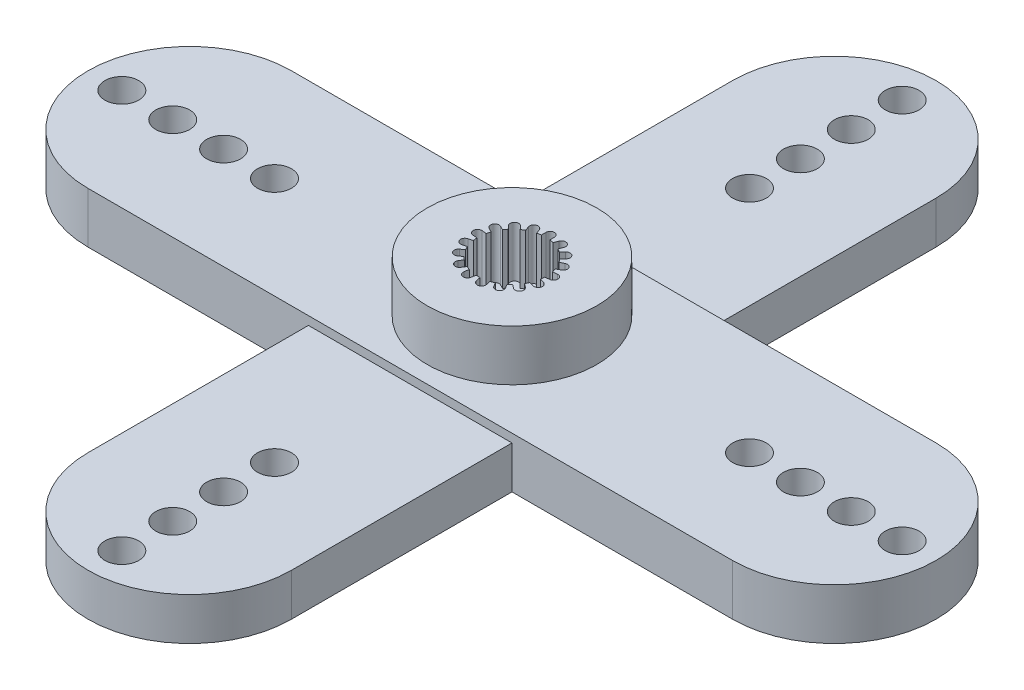
SolidWorks part; units mm, degrees
material "PP Homopolymer"
ref_plane "Front Plane" through (0, 0, 0) normal (0, 0, 1) x (1, 0, 0)
ref_plane "Top Plane" through (0, 0, 0) normal (0, 1, 0) x (1, 0, 0)
ref_plane "Right Plane" through (0, 0, 0) normal (1, 0, 0) x (0, 0, -1)
sketch "Sketch1" plane through (0, 0, 0) normal (0, 1, 0) x (1, 0, 0)
  circle A0 centre (0, 0) radius 5
  dimension "D1" = 10
extrude "Boss-Extrude1" add sketch "Sketch1" along normal blind 3
sketch "Sketch2" plane through (0, 0, 0) normal (0, -1, 0) x (1, 0, 0)
  line L0 (-19, 0) -> (19, 0) construction
  line L1 (-19, 6) -> (19, 6)
  line L2 (-19, -6) -> (19, -6)
  arc A0 (-19, 6) -> (-19, -6) centre (-19, 0) ccw
  arc A1 (19, -6) -> (19, 6) centre (19, 0) ccw
  point P2 (0, 0)
  dimension "D1" = 12
  dimension "D2" = 38
extrude "Boss-Extrude2" add sketch "Sketch2" along normal blind 3
sketch "Sketch3" plane through (0, -3, 0) normal (0, -1, 0) x (1, 0, 0)
  line L0 (0, -19) -> (0, 19) construction
  line L1 (-6, -19) -> (-6, 19)
  line L2 (6, -19) -> (6, 19)
  line L4 (19, 6) -> (-19, 6) construction
  arc A0 (-6, -19) -> (6, -19) centre (0, -19) ccw
  arc A1 (6, 19) -> (-6, 19) centre (0, 19) ccw
  arc A2 (19, -6) -> (19, 6) centre (19, 0) ccw construction
  point P2 (0, 0)
extrude "Boss-Extrude3" add sketch "Sketch3" against normal blind 2.5
sketch "Sketch4" plane through (0, -3, 0) normal (0, -1, 0) x (1, 0, 0)
  circle A0 centre (0, 0) radius 3
  dimension "D1" = 6
extrude "Cut-Extrude1" cut sketch "Sketch4" against normal blind 1
sketch "Sketch5" plane through (0, -2, 0) normal (0, -1, 0) x (1, 0, 0)
  circle A0 centre (0, 0) radius 1.25
  dimension "D1" = 2.5
extrude "Cut-Extrude2" cut sketch "Sketch5" against normal through all
sketch "Sketch6" plane through (0, 3, 0) normal (0, 1, 0) x (1, 0, 0)
  line L0 (0.25, 2.25) -> (0.25, 1.9843)
  line L1 (-0.25, 2.25) -> (-0.25, 1.9843)
  line L2 (0, 0) -> (0, 2.25) construction
  line L3 (1.0459, 2.0078) -> (0.9499, 1.76)
  line L4 (0.5797, 2.1884) -> (0.4837, 1.9406)
  line L5 (1.7006, 1.4943) -> (1.5216, 1.298)
  line L6 (1.3311, 1.8312) -> (1.1521, 1.6348)
  line L7 (2.1256, 0.7791) -> (1.8877, 0.6607)
  line L8 (1.9027, 1.2267) -> (1.6648, 1.1083)
  line L9 (2.2635, -0.0413) -> (1.9989, -0.0658)
  line L10 (2.2173, 0.4565) -> (1.9528, 0.432)
  line L11 (2.0957, -0.8562) -> (1.8401, -0.7835)
  line L12 (2.2325, -0.3753) -> (1.977, -0.3026)
  line L13 (1.6449, -1.5554) -> (1.4329, -1.3953)
  line L14 (1.9462, -1.1564) -> (1.7342, -0.9963)
  line L15 (0.9719, -2.0446) -> (0.8321, -1.8187)
  line L16 (1.397, -1.7814) -> (1.2572, -1.5555)
  line L17 (0.1677, -2.2576) -> (0.1189, -1.9965)
  line L18 (0.6592, -2.1658) -> (0.6104, -1.9046)
  line L19 (-0.6592, -2.1658) -> (-0.6104, -1.9046)
  line L20 (-0.1677, -2.2576) -> (-0.1189, -1.9965)
  line L21 (-1.397, -1.7814) -> (-1.2572, -1.5555)
  line L22 (-0.9719, -2.0446) -> (-0.8321, -1.8187)
  line L23 (-1.9462, -1.1564) -> (-1.7342, -0.9963)
  line L24 (-1.6449, -1.5554) -> (-1.4329, -1.3953)
  line L25 (-2.2325, -0.3753) -> (-1.977, -0.3026)
  line L26 (-2.0957, -0.8562) -> (-1.8401, -0.7835)
  line L27 (-2.2173, 0.4565) -> (-1.9528, 0.432)
  line L28 (-2.2635, -0.0413) -> (-1.9989, -0.0658)
  line L29 (-1.9027, 1.2267) -> (-1.6648, 1.1083)
  line L30 (-2.1256, 0.7791) -> (-1.8877, 0.6607)
  line L31 (-1.3311, 1.8312) -> (-1.1521, 1.6348)
  line L32 (-1.7006, 1.4943) -> (-1.5216, 1.298)
  line L33 (-0.5797, 2.1884) -> (-0.4837, 1.9406)
  line L34 (-1.0459, 2.0078) -> (-0.9499, 1.76)
  arc A0 (-0.25, 1.9843) -> (-0.4837, 1.9406) centre (0, 0) ccw
  arc A1 (0.25, 2.25) -> (-0.25, 2.25) centre (0, 2.25) ccw
  arc A2 (1.0459, 2.0078) -> (0.5797, 2.1884) centre (0.8128, 2.0981) ccw
  arc A3 (1.7006, 1.4943) -> (1.3311, 1.8312) centre (1.5158, 1.6628) ccw
  arc A4 (2.1256, 0.7791) -> (1.9027, 1.2267) centre (2.0141, 1.0029) ccw
  arc A5 (2.2635, -0.0413) -> (2.2173, 0.4565) centre (2.2404, 0.2076) ccw
  arc A6 (2.0957, -0.8562) -> (2.2325, -0.3753) centre (2.1641, -0.6157) ccw
  arc A7 (1.6449, -1.5554) -> (1.9462, -1.1564) centre (1.7955, -1.3559) ccw
  arc A8 (0.9719, -2.0446) -> (1.397, -1.7814) centre (1.1845, -1.913) ccw
  arc A9 (0.1677, -2.2576) -> (0.6592, -2.1658) centre (0.4134, -2.2117) ccw
  arc A10 (-0.6592, -2.1658) -> (-0.1677, -2.2576) centre (-0.4134, -2.2117) ccw
  arc A11 (-1.397, -1.7814) -> (-0.9719, -2.0446) centre (-1.1845, -1.913) ccw
  arc A12 (-1.9462, -1.1564) -> (-1.6449, -1.5554) centre (-1.7955, -1.3559) ccw
  arc A13 (-2.2325, -0.3753) -> (-2.0957, -0.8562) centre (-2.1641, -0.6157) ccw
  arc A14 (-2.2173, 0.4565) -> (-2.2635, -0.0413) centre (-2.2404, 0.2076) ccw
  arc A15 (-1.9027, 1.2267) -> (-2.1256, 0.7791) centre (-2.0141, 1.0029) ccw
  arc A16 (-1.3311, 1.8312) -> (-1.7006, 1.4943) centre (-1.5158, 1.6628) ccw
  arc A17 (-0.5797, 2.1884) -> (-1.0459, 2.0078) centre (-0.8128, 2.0981) ccw
  arc A18 (0.4837, 1.9406) -> (0.25, 1.9843) centre (0, 0) ccw
  arc A19 (1.1521, 1.6348) -> (0.9499, 1.76) centre (0, 0) ccw
  arc A20 (1.6648, 1.1083) -> (1.5216, 1.298) centre (0, 0) ccw
  arc A21 (1.9528, 0.432) -> (1.8877, 0.6607) centre (0, 0) ccw
  arc A22 (1.977, -0.3026) -> (1.9989, -0.0658) centre (0, 0) ccw
  arc A23 (-0.9499, 1.76) -> (-1.1521, 1.6348) centre (0, 0) ccw
  arc A24 (-1.5216, 1.298) -> (-1.6648, 1.1083) centre (0, 0) ccw
  arc A25 (-1.8877, 0.6607) -> (-1.9528, 0.432) centre (0, 0) ccw
  arc A26 (-1.9989, -0.0658) -> (-1.977, -0.3026) centre (0, 0) ccw
  arc A27 (-1.8401, -0.7835) -> (-1.7342, -0.9963) centre (0, 0) ccw
  arc A28 (-1.4329, -1.3953) -> (-1.2572, -1.5555) centre (0, 0) ccw
  arc A29 (-0.8321, -1.8187) -> (-0.6104, -1.9046) centre (0, 0) ccw
  arc A30 (-0.1189, -1.9965) -> (0.1189, -1.9965) centre (0, 0) ccw
  arc A31 (0.6104, -1.9046) -> (0.8321, -1.8187) centre (0, 0) ccw
  arc A32 (1.2572, -1.5555) -> (1.4329, -1.3953) centre (0, 0) ccw
  arc A33 (1.7342, -0.9963) -> (1.8401, -0.7835) centre (0, 0) ccw
  point P89 (0, 0)
  dimension "D1" = 4
  dimension "D2" = 0.5
  dimension "D3" = 2.25
  dimension "D4" = 17
extrude "Cut-Extrude3" cut sketch "Sketch6" against normal blind 3
sketch "Sketch7" plane through (0, -3, 0) normal (0, -1, 0) x (1, 0, 0)
  line L0 (0, 25) -> (0, -25) construction
  arc A0 (6, 19) -> (-6, 19) centre (0, 19) ccw construction
  arc A1 (-6, -19) -> (6, -19) centre (0, -19) ccw construction
  circle A2 centre (0, 23) radius 1
  circle A3 centre (0, 20) radius 1
  circle A4 centre (0, 17) radius 1
  circle A5 centre (0, 14) radius 1
  circle A6 centre (23, 0) radius 1
  circle A7 centre (20, 0) radius 1
  circle A8 centre (17, 0) radius 1
  circle A9 centre (14, 0) radius 1
  circle A10 centre (0, -23) radius 1
  circle A11 centre (0, -20) radius 1
  circle A12 centre (0, -17) radius 1
  circle A13 centre (0, -14) radius 1
  circle A14 centre (-23, 0) radius 1
  circle A15 centre (-20, 0) radius 1
  circle A16 centre (-17, 0) radius 1
  circle A17 centre (-14, 0) radius 1
  point P43 (0, 0)
  dimension "D1" = 2
  dimension "D2" = 3
  dimension "D3" = 2
  dimension "D4" = 3
  dimension "D5" = 3
  dimension "D6" = 4
extrude "Cut-Extrude4" cut sketch "Sketch7" against normal through all
